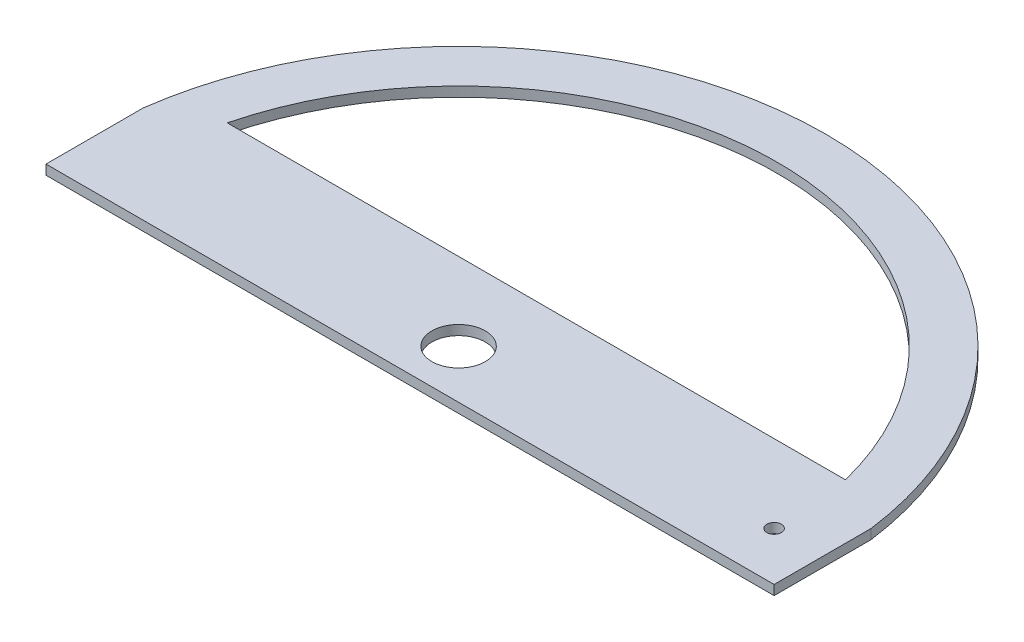
SolidWorks part; units mm, degrees
ref_plane "Front Plane" through (0, 0, 0) normal (0, 0, 1) x (1, 0, 0)
ref_plane "Top Plane" through (0, 0, 0) normal (0, 1, 0) x (1, 0, 0)
ref_plane "Right Plane" through (0, 0, 0) normal (1, 0, 0) x (0, 0, -1)
sketch "Sketch1" plane through (0, 0, 0) normal (0, 1, 0) x (1, 0, 0)
  line L0 (-63.6797, 16.0194) -> (63.6797, 16.0194)
  line L1 (75, -10) -> (-75, -10)
  line L2 (75, -10) -> (75, 10)
  line L4 (-75, -10) -> (-75, 10)
  line L5 (75, -10) -> (-75, 10) construction
  line L6 (75, 10) -> (-75, -10) construction
  arc A0 (75, 10) -> (-75, 10) centre (0, 0) ccw
  arc A1 (63.6797, 16.0194) -> (-63.6797, 16.0194) centre (0, 0) ccw
  arc A2 (65.0877, 8.6784) -> (-65.0877, 8.6784) centre (0, 0) ccw construction
  point P0 (0, 0)
  dimension "D1" = 20
  dimension "D2" = 150
  dimension "D3" = 10
extrude "Boss-Extrude1" add sketch "Sketch1" along normal blind 2
sketch "Sketch2" plane through (0, 2, 0) normal (0, 1, 0) x (1, 0, 0)
  line L0 (75, -10) -> (75, 10) construction
  circle A0 centre (0, 0) radius 5.5
  circle A1 centre (65, 0) radius 1.5
  point P5 (36.8881, -2.1434)
  point P6 (38.6931, 0)
  dimension "D1" = 11
  dimension "D2" = 3
  dimension "D3" = 10
extrude "Cut-Extrude1" cut sketch "Sketch2" against normal blind 2
